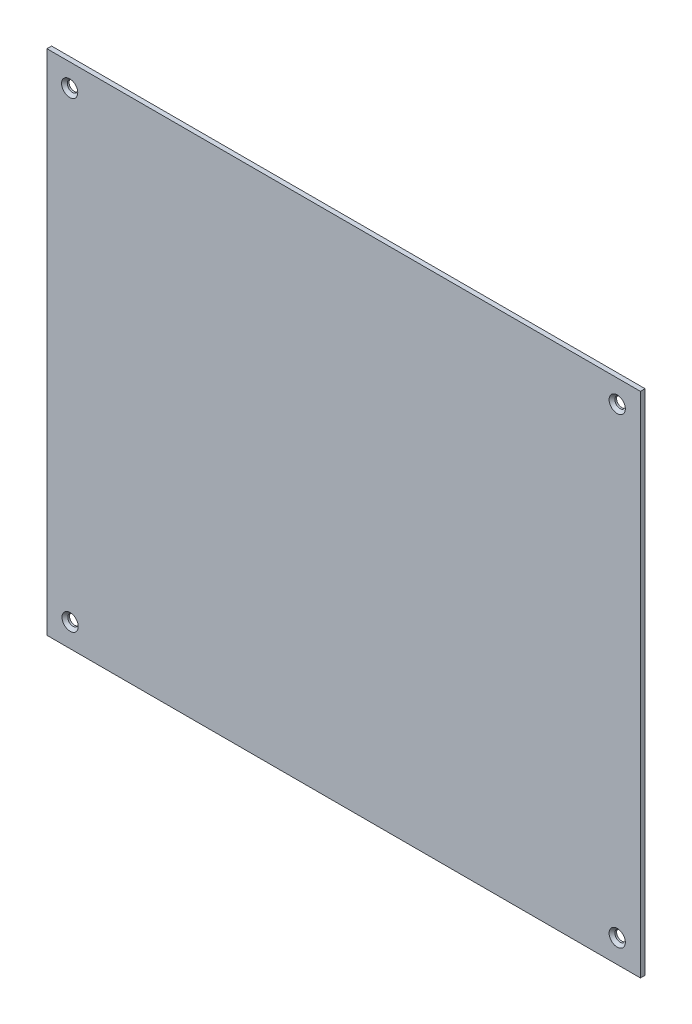
SolidWorks part; units mm, degrees
ref_plane "Front Plane" through (0, 0, 0) normal (0, 0, 1) x (1, 0, 0)
ref_plane "Top Plane" through (0, 0, 0) normal (0, 1, 0) x (1, 0, 0)
ref_plane "Right Plane" through (0, 0, 0) normal (1, 0, 0) x (0, 0, -1)
sketch "Sketch1" plane through (0, 0, 0) normal (0, 0, 1) x (1, 0, 0)
  line L1 (0, 0) -> (243.332, 0)
  line L2 (0, 0) -> (0, 208.28)
  line L3 (0, 208.28) -> (243.332, 208.28)
  line L11 (243.332, 0) -> (243.332, 208.28)
  dimension "D1" = 208.28
  dimension "D7" = 243.332
extrude "Boss-Extrude1" add sketch "Sketch1" along normal blind 1.905
sketch "Sketch4" plane through (0, 0, 1.905) normal (0, 0, 1) x (1, 0, 0)
  line L2 (233.807, 198.955) -> (243.332, 198.955) construction
  line L3 (243.332, 0) -> (243.332, 208.28) construction
  line L4 (233.807, 198.955) -> (233.807, 208.48) construction
  line L6 (0, 208.48) -> (243.332, 208.48) construction
  line L7 (0, 198.955) -> (9.325, 198.955) construction
  line L8 (0, 208.28) -> (0, 0) construction
  line L9 (9.325, 198.955) -> (9.325, 208.28) construction
  line L10 (243.332, 208.28) -> (0, 208.28) construction
  line L11 (0, 9.525) -> (9.525, 9.525) construction
  line L12 (9.525, 9.525) -> (9.525, 0) construction
  line L13 (0, 0) -> (243.332, 0) construction
  line L14 (233.807, 0) -> (233.807, 9.525) construction
  line L15 (233.807, 9.525) -> (243.332, 9.525) construction
  line L16 (243.332, 0) -> (243.332, 208.28) construction
  line L17 (0, 0) -> (243.332, 0) construction
  point P0 (9.325, 198.955)
  point P1 (233.807, 198.955)
  point P2 (233.807, 9.525)
  point P3 (9.525, 9.525)
  point P13 (233.807, 198.955)
  point P32 (9.525, 0)
  dimension "D2" = 9.525
hole_wizard "#6 Clearance Hole1" positions "Sketch4" profile "Sketch5" hole size "#6" standard "ANSI Inch" end condition up to next
sketch "Sketch5" plane through (9.325, 198.955, 1.905) normal (1, 0, 0) x (0, -1, 0)
  line L0 (0, 0) -> (0, 1.905)
  line L1 (0, 1.905) -> (2.1526, 1.905)
  line L2 (2.1526, 1.905) -> (2.1526, 1.1748)
  line L3 (2.1526, 1.1748) -> (3.3274, 0)
  line L5 (3.3274, 0) -> (0, 0)
  line L6 (-2.1526, 1.1747) -> (-3.3274, 0) construction
  line L11 (0, -6.35) -> (0, 107.95) construction
  dimension "Thru Hole Dia." = 4.3053
  dimension "Thru Hole Depth" = 1.905
  dimension "Near C'Sink Dia." = 6.6548
  dimension "Near C'Sink Angle" = 90
